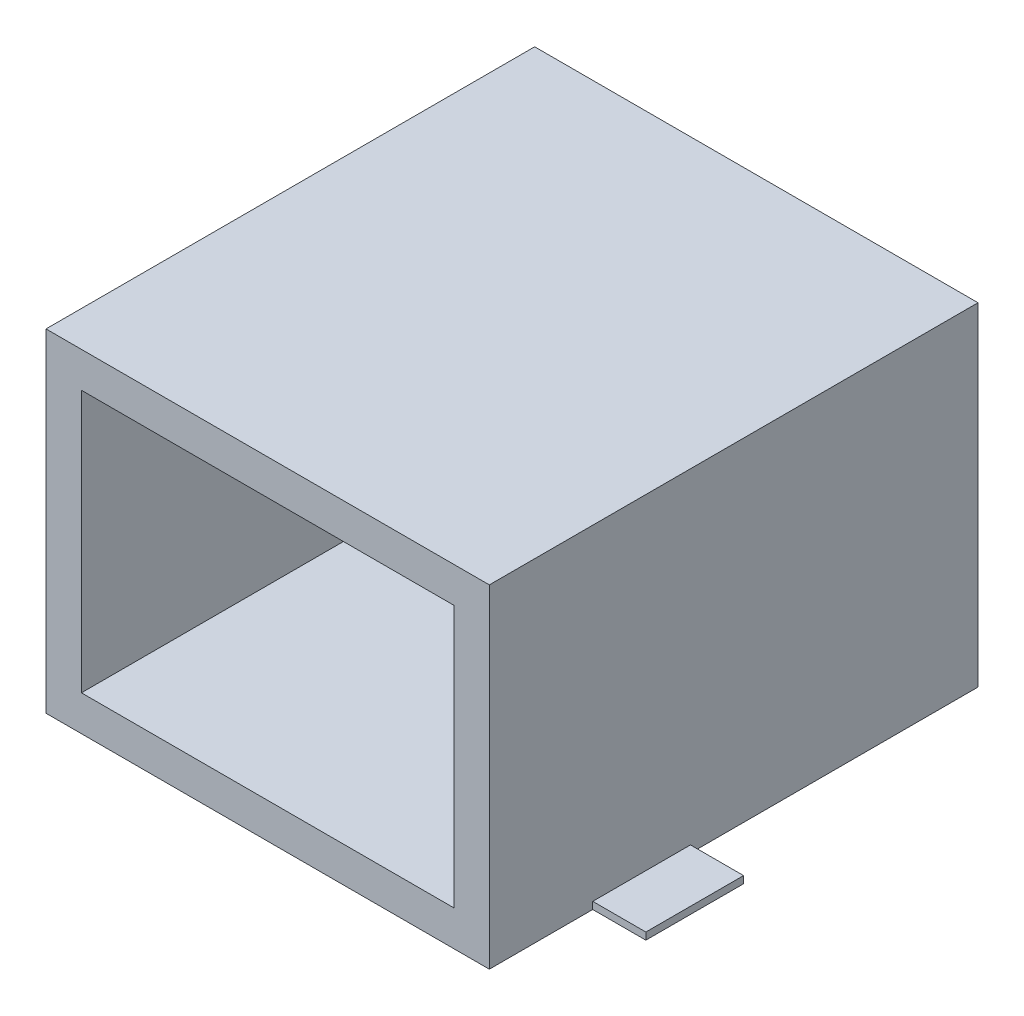
SolidWorks part; units mm, degrees
material "6061-T6 (SS)"
ref_plane "Front Plane" through (0, 0, 0) normal (0, 0, 1) x (1, 0, 0)
ref_plane "Top Plane" through (0, 0, 0) normal (0, 1, 0) x (1, 0, 0)
ref_plane "Right Plane" through (0, 0, 0) normal (1, 0, 0) x (0, 0, -1)
sketch "Sketch1" plane through (0, 0, 0) normal (0, 0, 1) x (1, 0, 0)
  line L1 (-7.9502, -5.969) -> (7.9502, -5.969)
  line L2 (-7.9502, -5.969) -> (-7.9502, 5.969)
  line L3 (-7.9502, 5.969) -> (7.9502, 5.969)
  line L4 (7.9502, -5.969) -> (7.9502, 5.969)
  line L5 (-7.9502, -5.969) -> (7.9502, 5.969) construction
  line L6 (-7.9502, 5.969) -> (7.9502, -5.969) construction
  point P0 (0, 0)
  dimension "D1" = 15.9004
  dimension "D2" = 11.938
extrude "Boss-Extrude1" add sketch "Sketch1" against normal blind 17.526
shell "Shell1" thickness 1.27
sketch "Sketch2" plane through (0, -5.969, 0) normal (0, -1, 0) x (1, 0, 0)
  line L0 (-7.9502, -17.526) -> (-7.9502, 0) construction
  line L1 (-7.9502, -3.7084) -> (-9.8552, -3.7084)
  line L2 (-7.9502, -3.7084) -> (-7.9502, -7.2136)
  line L3 (-7.9502, -7.2136) -> (-9.8552, -7.2136)
  line L4 (-9.8552, -3.7084) -> (-9.8552, -7.2136)
  line L5 (-7.9502, -5.461) -> (-12.1293, -5.461) construction
  line L6 (-7.9502, -17.526) -> (7.9502, -17.526) construction
  dimension "D1" = 12.065
  dimension "D2" = 3.5052
  dimension "D3" = 1.905
extrude "Boss-Extrude2" add sketch "Sketch2" against normal blind 0.254
mirror "Mirror1" about plane through (0, 0, 0) normal (1, 0, 0) of "Boss-Extrude2"
